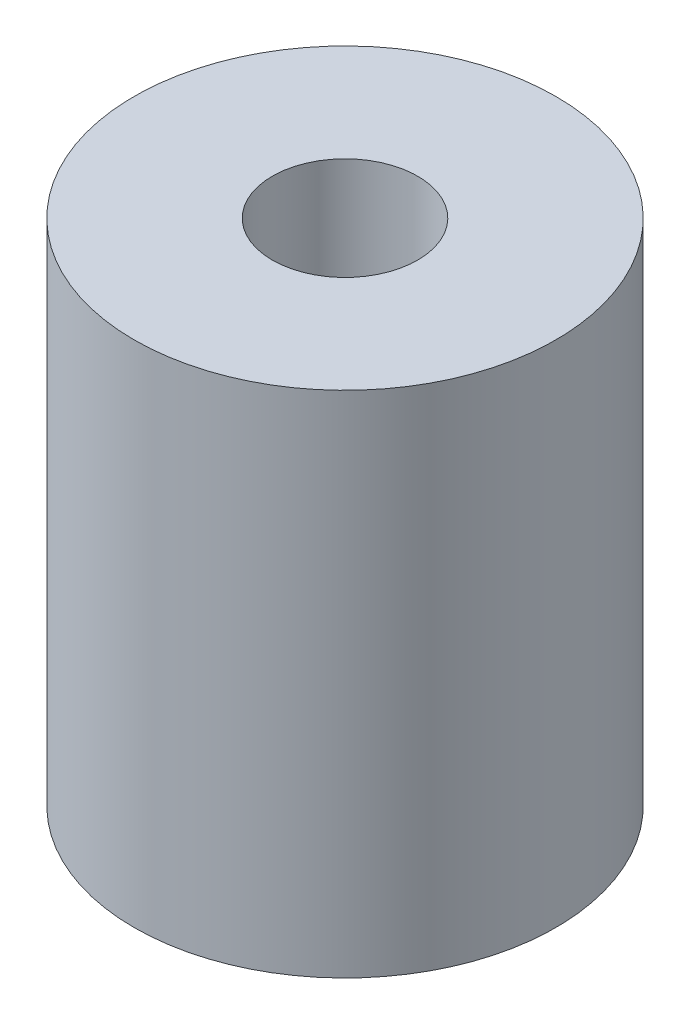
SolidWorks part; units mm, degrees
ref_plane "Front Plane" through (0, 0, 0) normal (0, 0, 1) x (1, 0, 0)
ref_plane "Top Plane" through (0, 0, 0) normal (0, 1, 0) x (1, 0, 0)
ref_plane "Right Plane" through (0, 0, 0) normal (1, 0, 0) x (0, 0, -1)
sketch "Sketch1" plane through (0, 0, 0) normal (0, 1, 0) x (1, 0, 0)
  circle A0 centre (0, 0) radius 14.5
  circle A1 centre (0, 0) radius 5
  dimension "D1" = 10
  dimension "D2" = 29
extrude "Boss-Extrude1" add sketch "Sketch1" along normal blind 35
